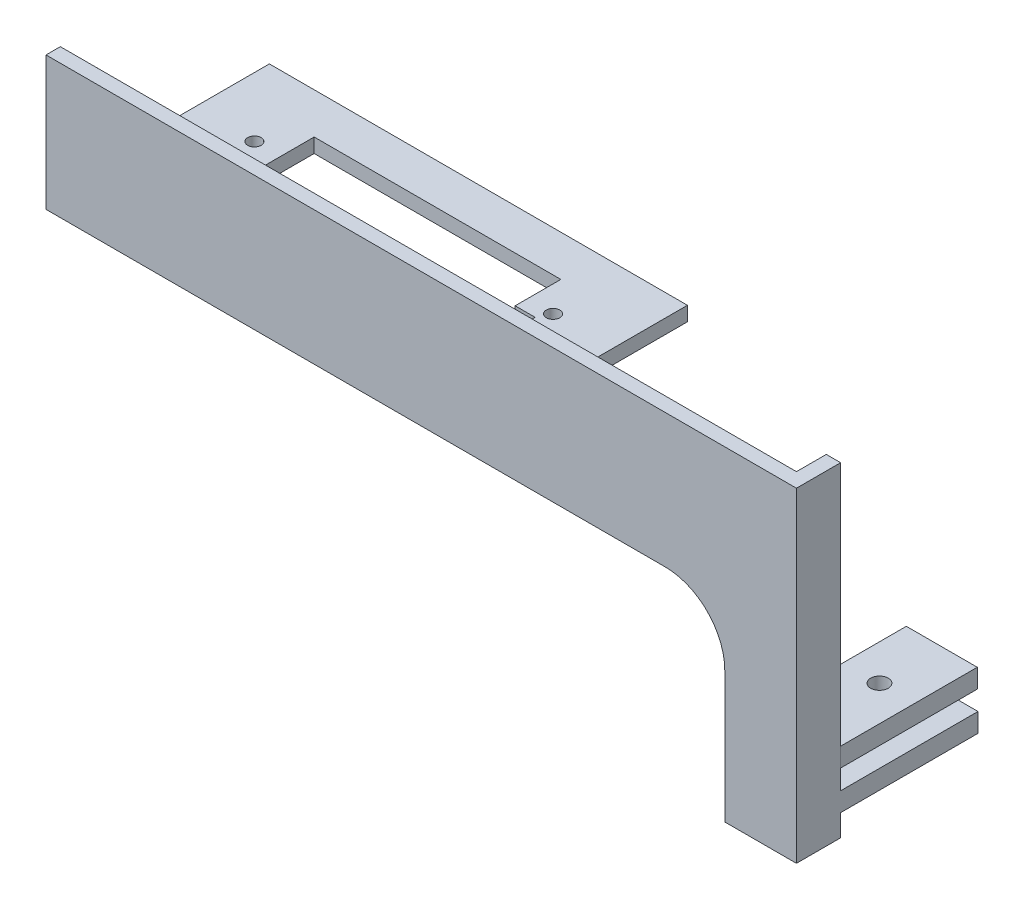
SolidWorks part; units mm, degrees
ref_plane "Front Plane" through (0, 0, 0) normal (0, 0, 1) x (1, 0, 0)
ref_plane "Top Plane" through (0, 0, 0) normal (0, 1, 0) x (1, 0, 0)
ref_plane "Right Plane" through (0, 0, 0) normal (1, 0, 0) x (0, 0, -1)
sketch "Sketch1" plane through (0, 0, 0) normal (0, 1, 0) x (1, 0, 0)
  line L1 (57.5229, 38.9958) -> (127.5229, 38.9958)
  line L2 (57.5229, 38.9958) -> (57.5229, 3.9958)
  line L3 (57.5229, 3.9958) -> (127.5229, 3.9958)
  line L4 (127.5229, 38.9958) -> (127.5229, 3.9958)
  dimension "D1" = 70
  dimension "D2" = 35
extrude "Boss-Extrude1" add sketch "Sketch1" along normal blind 2.4
sketch "Sketch2" plane through (0, 2.4, 0) normal (0, 1, 0) x (1, 0, 0)
  line L1 (127.5229, 38.9958) -> (57.5229, 38.9958) construction
  line L2 (57.5229, 21.4958) -> (127.5229, 21.4958) construction
  line L3 (57.5229, 38.9958) -> (57.5229, 3.9958) construction
  line L4 (127.5229, 3.9958) -> (127.5229, 38.9958) construction
  line L5 (112.5229, 38.9958) -> (112.5229, 3.9958) construction
  line L6 (57.5229, 3.9958) -> (127.5229, 3.9958) construction
  line L7 (72.5229, 38.9958) -> (72.5229, 3.9958) construction
  line L9 (72.5229, 31.4958) -> (112.5229, 31.4958)
  line L10 (72.5229, 31.4958) -> (72.5229, 11.4958)
  line L11 (72.5229, 11.4958) -> (112.5229, 11.4958)
  line L12 (112.5229, 31.4958) -> (112.5229, 11.4958)
  circle A0 centre (67.5229, 26.4958) radius 1.13
  circle A1 centre (117.5229, 26.4958) radius 1.13
  circle A2 centre (117.5229, 16.4958) radius 1.13
  circle A3 centre (67.5229, 16.4958) radius 1.13
  point P37 (57.5229, 21.4958)
  dimension "D5" = 2.26
  dimension "D6" = 2.26
  dimension "D19" = 20
  dimension "D2" = 15
  dimension "D3" = 40
  dimension "D4" = 10
  dimension "D7" = 5
  dimension "D8" = 5
  dimension "D9" = 5
  dimension "D10" = 5
extrude "Cut-Extrude1" cut sketch "Sketch2" against normal blind 2.4
sketch "Sketch4" plane through (0, 2.4, 0) normal (0, 1, 0) x (1, 0, 0)
  line L0 (72.5229, 21.4958) -> (127.5229, 21.4958) construction
  line L1 (72.5229, 31.4958) -> (72.5229, 11.4958) construction
  line L2 (127.5229, 3.9958) -> (127.5229, 38.9958) construction
  line L3 (112.5229, 11.4958) -> (112.5229, 31.4958) construction
  line L4 (112.5229, 24.4958) -> (116.5229, 24.4958)
  line L5 (112.5229, 24.4958) -> (112.5229, 18.4958)
  line L6 (112.5229, 18.4958) -> (116.5229, 18.4958)
  line L7 (116.5229, 24.4958) -> (116.5229, 18.4958)
  dimension "D1" = 6
  dimension "D2" = 3
  dimension "D3" = 4
extrude "Cut-Extrude2" cut sketch "Sketch4" against normal blind 2.4
sketch "Sketch7" plane through (0, 2.4, 0) normal (0, 1, 0) x (1, 0, 0)
  line L0 (71.8729, 32.1458) -> (71.8729, 10.8458)
  line L1 (72.5229, 31.4958) -> (112.5229, 31.4958)
  line L2 (72.5229, 31.4958) -> (72.5229, 11.4958)
  line L3 (72.5229, 11.4958) -> (112.5229, 11.4958)
  line L4 (112.5229, 31.4958) -> (112.5229, 11.4958)
  line L5 (71.8729, 10.8458) -> (113.1729, 10.8458)
  line L6 (113.1729, 32.1458) -> (113.1729, 10.8458)
  line L7 (71.8729, 32.1458) -> (113.1729, 32.1458)
  dimension "D1" = 0.65
extrude "Cut-Extrude3" cut sketch "Sketch7" against normal through all both and the other way through all
sketch "Sketch8" plane through (0, 0, -3.9958) normal (0, 0, 1) x (1, 0, 0)
  line L6 (57.5229, 22.4) -> (183.1729, 22.4)
  line L7 (113.1729, 0) -> (113.1729, 2.4) construction
  line L8 (177.1729, 27.5563) -> (177.1729, -42.617) construction
  line L9 (57.5229, 0) -> (57.5229, 22.4)
  line L10 (183.1729, 22.4) -> (183.1729, -32)
  line L11 (183.1729, -32) -> (171.1729, -32)
  line L12 (171.1729, -32) -> (171.1729, 0)
  line L13 (171.1729, 0) -> (57.5229, 0)
  line L14 (57.5229, 2.4) -> (127.5229, 2.4) construction
  line L15 (163.7402, -22) -> (194.5121, -22) construction
  point P13 (113.1729, 1.2)
  dimension "D1" = 6
  dimension "D2" = 6
  dimension "D3" = 20
  dimension "D4" = 64
  dimension "D5" = 22
  dimension "D6" = 10
extrude "Boss-Extrude2" add sketch "Sketch8" along normal blind 2.4
sketch "Sketch9" plane through (0, 0, -3.9958) normal (0, 0, -1) x (-1, 0, 0)
  line L0 (-127.5229, 0) -> (-210.0115, 0) construction
  line L1 (-211.5009, -22) -> (-127.5229, -22) construction
  line L2 (-171.1729, 0) -> (-171.1729, -32) construction
  line L3 (-183.0529, -22) -> (-171.1729, -22)
  line L4 (-183.0529, -22) -> (-183.0529, -18.825)
  line L5 (-183.0529, -18.825) -> (-171.1729, -18.825)
  line L6 (-171.1729, -22) -> (-171.1729, -18.825)
  line L7 (-183.1729, -32) -> (-183.1729, 22.4) construction
  line L8 (-183.1729, -25.175) -> (-171.1729, -25.175)
  line L9 (-183.1729, -25.175) -> (-183.1729, -28.35)
  line L10 (-183.1729, -28.35) -> (-171.1729, -28.35)
  line L11 (-171.1729, -25.175) -> (-171.1729, -28.35)
  dimension "D1" = 22
  dimension "D2" = 3.175
  dimension "D3" = 3.175
  dimension "D4" = 3.175
extrude "Boss-Extrude3" add sketch "Sketch9" along normal blind 28
sketch "Sketch10" plane through (0, -28.35, 0) normal (0, -1, 0) x (1, 0, 0)
  line L0 (177.1729, -31.9958) -> (177.1729, 13.7377) construction
  line L1 (183.1729, -31.9958) -> (171.1729, -31.9958) construction
  line L2 (157.8815, -21.4958) -> (208.671, -21.4958) construction
  line L3 (127.5229, -3.9958) -> (171.1729, -3.9958) construction
  circle A0 centre (177.1729, -21.4958) radius 1.4732
  dimension "D2" = 2.9464
  dimension "D1" = 17.5
extrude "Cut-Extrude4" cut sketch "Sketch10" against normal blind 30
fillet "Fillet1" radius 10 1 edges at (171.1729, 0, -2.7958)
sketch "Sketch11" plane through (183.1729, 0, 0) normal (1, 0, 0) x (0, 0, -1)
  line L6 (3.9958, 22.4) -> (8.9958, 22.4)
  line L7 (3.9958, 22.4) -> (3.9958, -32)
  line L8 (3.9958, -32) -> (8.9958, -32)
  line L9 (8.9958, 22.4) -> (8.9958, -32)
  dimension "D1" = 5
extrude "Boss-Extrude4" add sketch "Sketch11" against normal blind 2.4
